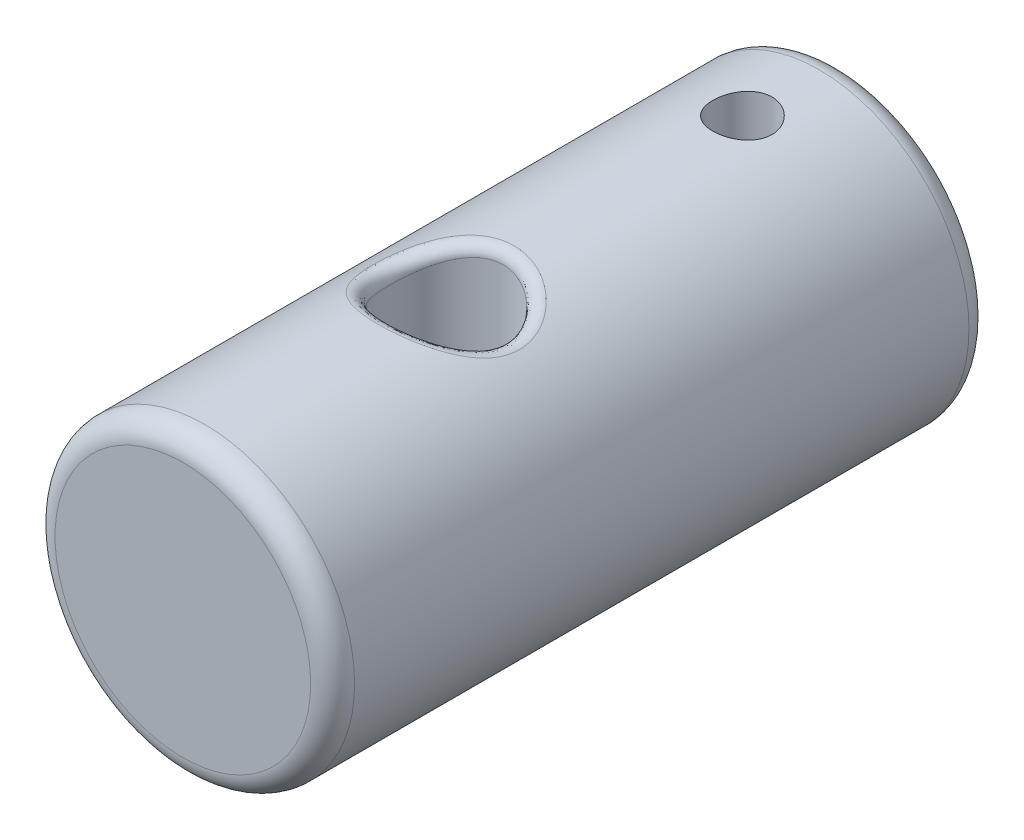
SolidWorks part; units mm, degrees
ref_plane "Front Plane" through (0, 0, 0) normal (0, 0, 1) x (1, 0, 0)
ref_plane "Top Plane" through (0, 0, 0) normal (0, 1, 0) x (1, 0, 0)
ref_plane "Right Plane" through (0, 0, 0) normal (1, 0, 0) x (0, 0, -1)
sketch "Sketch1" plane through (0, 0, 0) normal (0, 0, 1) x (1, 0, 0)
  circle A0 centre (0, 0) radius 6.825
  dimension "D1" = 13.65
extrude "Boss-Extrude1" add sketch "Sketch1" along normal blind 12 and the other way blind 18
sketch "Sketch2" plane through (0, 0, 0) normal (0, 1, 0) x (1, 0, 0)
  circle A0 centre (0, 0) radius 2.6
  circle A1 centre (0, 13.5) radius 1.35 construction
  circle A2 centre (0, 13.5) radius 1.35
  dimension "D1" = 5.2
extrude "Cut-Extrude1" cut sketch "Sketch2" against normal through all and the other way through all
fillet "Fillet1" radius 1 2 edges at (6.825, 0, -18) (6.825, 0, 12)
fillet "Fillet2" radius 0.5 2 edges at (0.3965, -6.8135, -2.5696) (-0.3965, 6.8135, -2.5696)
